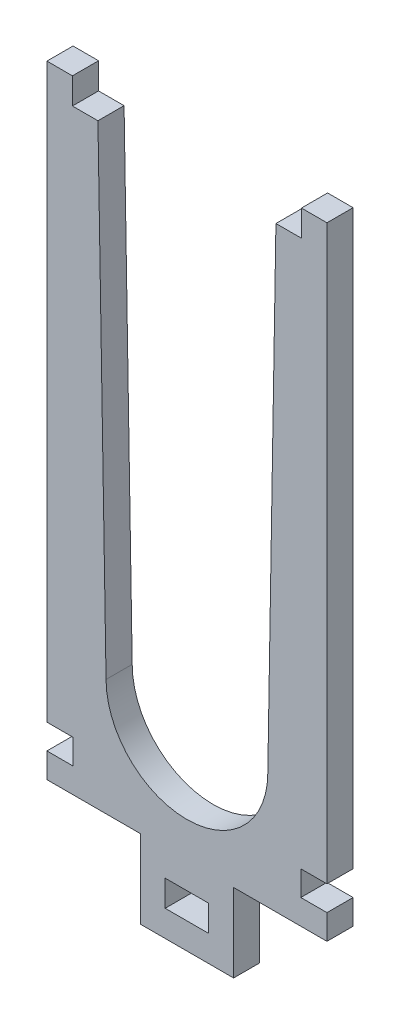
SolidWorks part; units mm, degrees
ref_plane "Front Plane" through (0, 0, 0) normal (0, 0, 1) x (1, 0, 0)
ref_plane "Top Plane" through (0, 0, 0) normal (0, 1, 0) x (1, 0, 0)
ref_plane "Right Plane" through (0, 0, 0) normal (1, 0, 0) x (0, 0, -1)
sketch "Sketch8" plane through (0, 0, 0) normal (0, 0, 1) x (1, 0, 0)
  line L1 (0, 0) -> (57.15, 0)
  line L2 (0, 0) -> (0, 127)
  line L3 (0, 127) -> (57.15, 127)
  line L4 (57.15, 0) -> (57.15, 127)
  dimension "D1" = 57.15
  dimension "D2" = 127
extrude "Boss-Extrude3" add sketch "Sketch8" along normal blind 5.334
sketch "Sketch9" plane through (0, 0, 5.334) normal (0, 0, 1) x (1, 0, 0)
  line L0 (0, 127) -> (10.414, 127)
  line L1 (57.15, 127) -> (0, 127) construction
  line L2 (28.575, 0) -> (28.575, 12.573) construction
  line L3 (57.15, 127) -> (46.736, 127)
  line L4 (57.15, 127) -> (46.736, 127)
  line L5 (0, 0) -> (57.15, 0) construction
  line L6 (28.575, 29.083) -> (28.575, 12.573) construction
  line L7 (10.414, 127) -> (12.0698, 29.083)
  line L8 (46.736, 127) -> (45.0802, 29.083)
  circle A0 centre (28.575, 29.083) radius 16.5052
  line M9 (57.15, 127) -> (0, 127)
  dimension "D1" = 10.414
  dimension "D2" = 10.414
  dimension "D3" = 12.573
  dimension "D4" = 16.51
extrude "Cut-Extrude4" cut sketch "Sketch9" against normal through all contours A0 L8 L7 M9 | A0
sketch "Sketch12" plane through (0, 0, 0) normal (0, -1, 0) x (-1, 0, 0)
  line L0 (0, -5.334) -> (-57.15, -5.334) construction
  line L1 (-57.15, 0) -> (-38.1, 0)
  line L2 (-57.15, 0) -> (-57.15, -5.334)
  line L3 (-57.15, -5.334) -> (-38.1, -5.334)
  line L4 (-38.1, 0) -> (-38.1, -5.334)
  line L5 (-38.1, -5.334) -> (-19.05, -5.334) construction
  line L6 (0, 0) -> (-19.05, 0)
  line L7 (0, 0) -> (0, -5.334)
  line L8 (0, -5.334) -> (-19.05, -5.334)
  line L9 (-19.05, 0) -> (-19.05, -5.334)
extrude "Cut-Extrude8" cut sketch "Sketch12" against normal blind 5.334
sketch "Sketch14" plane through (0, 127, 0) normal (0, 1, 0) x (1, 0, 0)
  line L1 (46.736, 0) -> (57.15, 0)
  line L2 (46.736, 0) -> (46.736, -5.334)
  line L3 (46.736, -5.334) -> (57.15, -5.334)
  line L4 (57.15, 0) -> (57.15, -5.334)
  line L5 (0, 0) -> (10.414, 0)
  line L6 (0, 0) -> (0, -5.334)
  line L7 (0, -5.334) -> (10.414, -5.334)
  line L8 (10.414, 0) -> (10.414, -5.334)
extrude "Boss-Extrude4" add sketch "Sketch14" along normal blind 5.334
sketch "Sketch15" plane through (0, 132.334, 0) normal (0, 1, 0) x (1, 0, 0)
  line L0 (0, -5.334) -> (10.414, -5.334) construction
  line L1 (10.414, 0) -> (5.207, 0)
  line L2 (10.414, 0) -> (10.414, -5.334)
  line L3 (10.414, -5.334) -> (5.207, -5.334)
  line L4 (5.207, 0) -> (5.207, -5.334)
  line L5 (5.207, 0) -> (0, 0) construction
  line L6 (46.736, -5.334) -> (57.15, -5.334) construction
  line L7 (46.736, 0) -> (51.943, 0)
  line L8 (46.736, 0) -> (46.736, -5.334)
  line L9 (46.736, -5.334) -> (51.943, -5.334)
  line L10 (51.943, 0) -> (51.943, -5.334)
  line L11 (51.943, 0) -> (57.15, 0) construction
extrude "Cut-Extrude9" cut sketch "Sketch15" against normal blind 5.334
sketch "Sketch22" plane through (0, 0, 0) normal (0, -1, 0) x (1, 0, 0)
  line L1 (38.1, 0) -> (19.05, 0)
  line L2 (38.1, 0) -> (38.1, 5.334)
  line L3 (38.1, 5.334) -> (19.05, 5.334)
  line L4 (19.05, 0) -> (19.05, 5.334)
extrude "Boss-Extrude5" add sketch "Sketch22" along normal blind 10.668
sketch "Sketch23" plane through (0, 0, 0) normal (0, 0, -1) x (-1, 0, 0)
  line L0 (-19.05, -10.668) -> (-38.1, -10.668) construction
  line L1 (-33.02, 0) -> (-24.13, 0)
  line L2 (-33.02, 0) -> (-33.02, -5.334)
  line L3 (-33.02, -5.334) -> (-24.13, -5.334)
  line L4 (-24.13, 0) -> (-24.13, -5.334)
  line L5 (-19.05, 5.334) -> (-19.05, -10.668) construction
  line L6 (-38.1, 5.334) -> (-38.1, -10.668) construction
  dimension "D1" = 5.334
  dimension "D2" = 5.334
  dimension "D3" = 5.08
  dimension "D4" = 8.89
  dimension "D5" = 5.08
extrude "Cut-Extrude15" cut sketch "Sketch23" against normal through all
sketch "Sketch24" plane through (0, 0, 0) normal (0, 0, -1) x (-1, 0, 0)
  line L0 (-57.15, 5.334) -> (0, 5.334) construction
  line L1 (-28.575, 5.334) -> (-28.575, 23.0561) construction
  line L2 (-57.15, 5.334) -> (-57.15, 132.334) construction
  line L3 (-57.15, 10.414) -> (-51.816, 10.414)
  line L4 (-57.15, 10.414) -> (-57.15, 15.494)
  line L5 (-57.15, 15.494) -> (-51.816, 15.494)
  line L6 (-51.816, 10.414) -> (-51.816, 15.494)
  line L7 (-5.334, 10.414) -> (-5.334, 15.494)
  line L8 (0, 15.494) -> (-5.334, 15.494)
  line L9 (0, 10.414) -> (0, 15.494)
  line L10 (0, 10.414) -> (-5.334, 10.414)
  dimension "D1" = 5.08
  dimension "D2" = 5.08
  dimension "D3" = 5.334
extrude "Cut-Extrude16" cut sketch "Sketch24" against normal through all
equation "\"Foamcore\"= .1875in"
equation "\"Mdf\"= .21in"
equation "\"Gmaterial\"= \"Mdf\""
equation "\"D1@Boss-Extrude3\"= \"Gmaterial\""
equation "\"D1@Cut-Extrude9\"=\"Gmaterial\""
equation "\"D1@Cut-Extrude8\"=\"Gmaterial\""
equation "\"D1@Boss-Extrude4\"= \"Gmaterial\""
equation "\"D2@Sketch9\"=0.41in"
equation "\"D1@Sketch9\"=0.41in"
equation "\"D2@Sketch8\"=5in"
equation "\"D3@Sketch9\"=0.495in"
